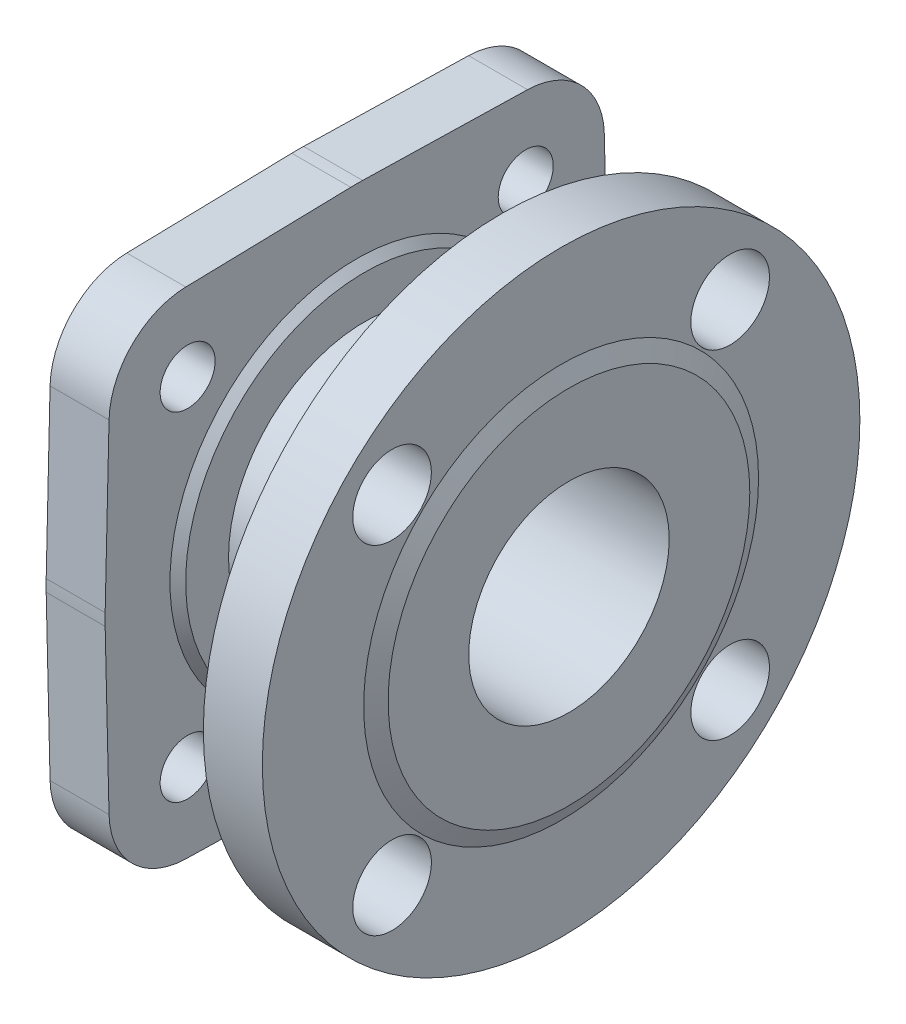
SolidWorks part; units mm, degrees
ref_plane "Front Plane" through (0, 0, 0) normal (0, 0, 1) x (1, 0, 0)
ref_plane "Top Plane" through (0, 0, 0) normal (0, 1, 0) x (1, 0, 0)
ref_plane "Right Plane" through (0, 0, 0) normal (1, 0, 0) x (0, 0, -1)
sketch "Sketch2" plane through (0, 0, 0) normal (1, 0, 0) x (0, 0, -1)
  line L0 (-34.6014, 0) -> (39.9867, 0) construction
  line L1 (0, 31.0763) -> (0, -32.0367) construction
  line L2 (62.9945, 43.4707) -> (63.9823, 1.5061)
  line L3 (-43.4707, 62.9945) -> (-1.5061, 63.9823)
  line L4 (43.4707, 62.9945) -> (1.5061, 63.9823)
  line L5 (-62.9945, 43.4707) -> (-63.9823, 1.5061)
  line L6 (43.4707, -62.9945) -> (1.5061, -63.9823)
  line L7 (-43.4707, -62.9945) -> (-1.5061, -63.9823)
  line L8 (62.9945, -43.4707) -> (63.9823, -1.5061)
  line L9 (-62.9945, -43.4707) -> (-63.9823, -1.5061)
  arc A0 (-63.9823, 1.5061) -> (-63.9823, -1.5061) centre (0, 0) ccw
  arc A2 (62.9945, 43.4707) -> (43.4707, 62.9945) centre (43, 43) ccw
  arc A7 (-62.9945, 43.4707) -> (-43.4707, 62.9945) centre (-43, 43) cw
  arc A9 (1.5061, 63.9823) -> (-1.5061, 63.9823) centre (0, 0) ccw
  arc A10 (1.5061, -63.9823) -> (-1.5061, -63.9823) centre (0, 0) cw
  arc A12 (-62.9945, -43.4707) -> (-43.4707, -62.9945) centre (-43, -43) ccw
  arc A13 (62.9945, -43.4707) -> (43.4707, -62.9945) centre (43, -43) cw
  arc A15 (-1.5061, -63.9823) -> (1.5061, -63.9823) centre (0, 0) ccw
  arc A17 (63.9823, -1.5061) -> (63.9823, 1.5061) centre (0, 0) ccw
  dimension "D1" = 128
  dimension "D3" = 40
  dimension "D4" = 43
  dimension "D5" = 43
extrude "Boss-Extrude1" add sketch "Sketch2" along normal blind 15 contours L8 A17 L2 A2 L4 A9 L3 A7 L5 A0 L9 A12 L7 A10 L6 A13
sketch "Sketch3" plane through (15, 0, 0) normal (1, 0, 0) x (0, 0, -1)
  line L0 (-13.4201, 0) -> (17.9234, 0) construction
  line L1 (0, 20.2652) -> (0, -16.4824) construction
  circle A0 centre (-43, 43) radius 7
  arc A1 (-43.4707, 62.9945) -> (-62.9945, 43.4707) centre (-43, 43) ccw construction
  circle A2 centre (43, 43) radius 7
  circle A3 centre (43, -43) radius 7
  circle A4 centre (-43, -43) radius 7
  dimension "D1" = 14
extrude "Cut-Extrude1" cut sketch "Sketch3" against normal blind 15
sketch "Sketch4" plane through (0, 0, 0) normal (0, 0, 1) x (1, 0, 0)
  line L0 (15, 0) -> (15, 47.5)
  line L1 (15, -1.5061) -> (15, 1.5061) construction
  line L2 (15, 43.4707) -> (15, 1.5061) construction
  line L3 (15, 47.5) -> (17, 45.5)
  line L4 (17, 45.5) -> (17, 34.6)
  line L5 (17, 34.6) -> (34, 34.6)
  line L6 (34, 34.6) -> (52, 39.4231)
  line L7 (52, 39.4231) -> (52, 76)
  line L8 (52, 76) -> (67, 76)
  line L9 (67, 76) -> (67, 50.2283)
  line L10 (67, 50.2283) -> (69, 46)
  line L11 (69, 46) -> (69, 0)
  line L12 (69, 0) -> (15, 0)
  line L13 (0, 43.4707) -> (0, 1.5061) construction
  line L14 (0, 62.9945) -> (0, 43.4707) construction
  point P19 (67, 50.2283)
  dimension "D1" = 34.6
  dimension "D2" = 47.5
  dimension "D3" = 34
  dimension "D4" = 15
  dimension "D5" = 67
  dimension "D6" = 45
  dimension "D7" = 46
  dimension "D8" = 76
  dimension "D9" = 2
  dimension "D10" = 2
  dimension "D11" = 15
revolve "Revolve1" add sketch "Sketch4" angle 360 about L12
sketch "Sketch7" plane through (69, 0, 0) normal (1, 0, 0) x (0, 0, -1)
  circle A0 centre (0, 0) radius 25.5
  dimension "D1" = 51
extrude "Cut-Extrude2" cut sketch "Sketch7" against normal through all
sketch "Sketch10" plane through (67, 0, 0) normal (1, 0, 0) x (0, 0, -1)
  line L0 (0, 16.578) -> (0, -14.0111) construction
  line L1 (-16.6862, 0) -> (17.3255, 0) construction
  circle A0 centre (-43, 43) radius 10
  circle A1 centre (-43, 43) radius 7 construction
  circle A2 centre (43, 43) radius 10
  circle A3 centre (43, -43) radius 10
  circle A4 centre (-43, -43) radius 10
  dimension "D1" = 20
extrude "Cut-Extrude3" cut sketch "Sketch10" against normal blind 25
